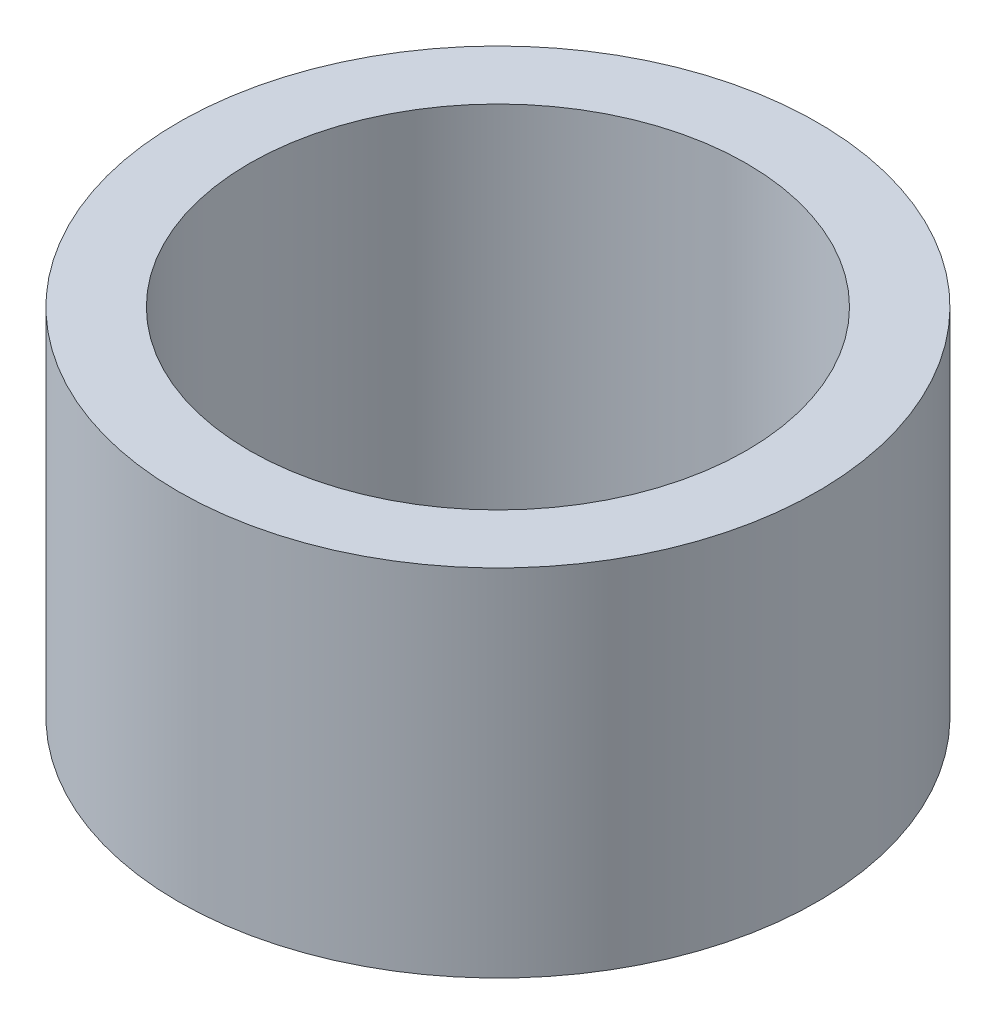
SolidWorks part; units mm, degrees
ref_plane "Front Plane" through (0, 0, 0) normal (0, 0, 1) x (1, 0, 0)
ref_plane "Top Plane" through (0, 0, 0) normal (0, 1, 0) x (1, 0, 0)
ref_plane "Right Plane" through (0, 0, 0) normal (1, 0, 0) x (0, 0, -1)
sketch "Sketch1" plane through (0, 0, 0) normal (0, 1, 0) x (1, 0, 0)
  circle A1 centre (0, 0) radius 17.5
  circle A2 centre (0, 0) radius 22.5
  dimension "D1" = 35
  dimension "D2" = 5
extrude "Boss-Extrude1" add sketch "Sketch1" along normal blind 25
